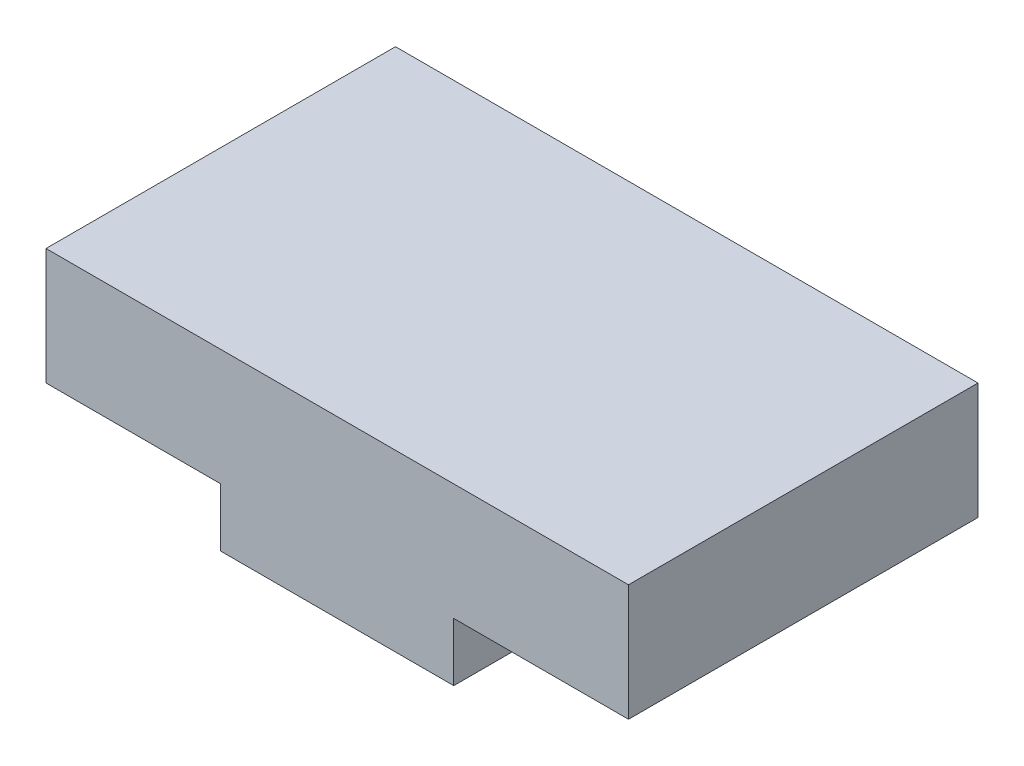
SolidWorks part; units mm, degrees
ref_plane "Front Plane" through (0, 0, 0) normal (0, 0, 1) x (1, 0, 0)
ref_plane "Top Plane" through (0, 0, 0) normal (0, 1, 0) x (1, 0, 0)
ref_plane "Right Plane" through (0, 0, 0) normal (1, 0, 0) x (0, 0, -1)
sketch "Sketch1" plane through (0, 0, 0) normal (0, 0, 1) x (1, 0, 0)
  line L0 (10, -5) -> (25, -5)
  line L1 (-25, 5) -> (25, 5)
  line L2 (-25, 5) -> (-25, -5)
  line L3 (-25, -5) -> (-10, -5)
  line L4 (25, 5) -> (25, -5)
  line L5 (-10, -5) -> (-10, -10)
  line L6 (-10, -10) -> (10, -10)
  line L7 (10, -5) -> (10, -10)
  point P0 (0, 0)
  point P5 (0, -8.7396)
  point P7 (0, 5)
  point P9 (0, -10)
  point P11 (-25, 0)
  point P13 (25, 0)
  dimension "D1" = 50
  dimension "D2" = 10
  dimension "D3" = 15
  dimension "D4" = 5
extrude "Boss-Extrude1" add sketch "Sketch1" along normal mid plane 30
